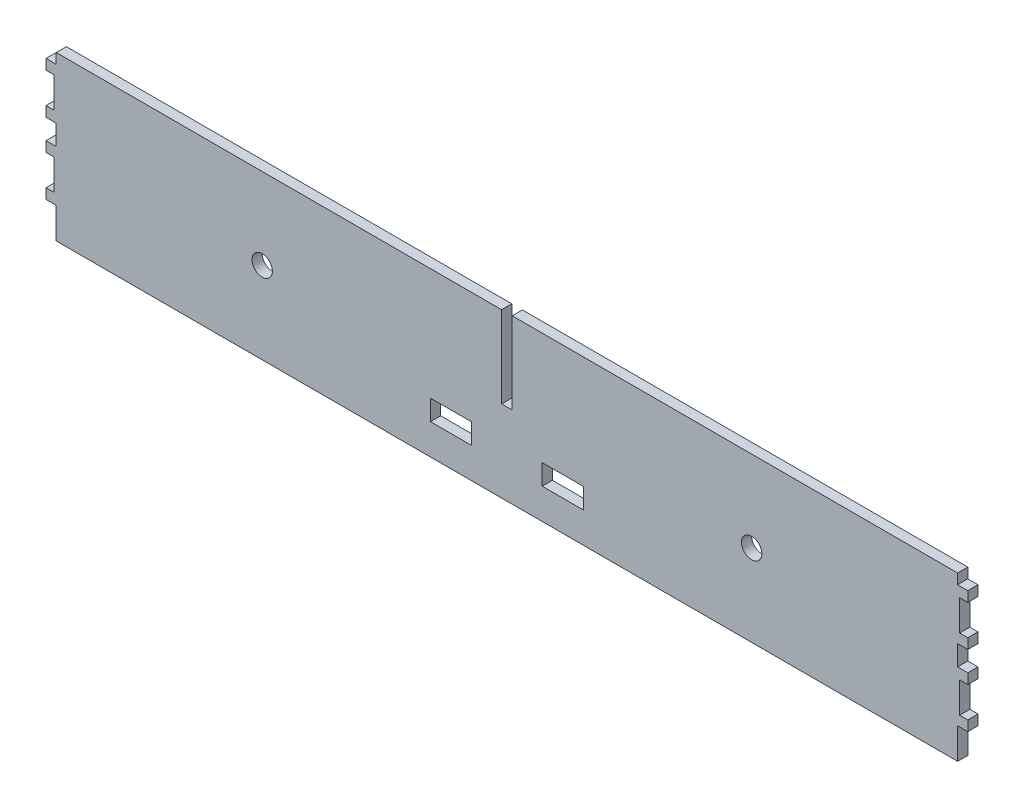
SolidWorks part; units mm, degrees
ref_plane "Front Plane" through (0, 0, 0) normal (0, 0, 1) x (1, 0, 0)
ref_plane "Top Plane" through (0, 0, 0) normal (0, 1, 0) x (1, 0, 0)
ref_plane "Right Plane" through (0, 0, 0) normal (1, 0, 0) x (0, 0, -1)
sketch "Sketch1" plane through (0, 0, 0) normal (0, 0, 1) x (1, 0, 0)
  line L1 (-221, 80) -> (221, 80)
  line L2 (-221, 80) -> (-221, 0)
  line L3 (-221, 0) -> (221, 0)
  line L4 (221, 80) -> (221, 0)
  point P4 (0, 0)
  dimension "D1" = 442
  dimension "D2" = 80
extrude "Boss-Extrude1" add sketch "Sketch1" along normal mid plane 5
sketch "Sketch2" plane through (0, 0, 0) normal (0, 0, 1) x (1, 0, 0)
  line L0 (-221, 0) -> (221, 0) construction
  line L1 (60, 0) -> (-60, 0)
  line L2 (60, 0) -> (60, 8.3333)
  line L3 (58.3333, 10) -> (-58.3333, 10)
  line L4 (-60, 0) -> (-60, 8.3333)
  line L13 (0, -55) -> (0, 55) construction
  arc A3 (-60, 8.3333) -> (-58.3333, 10) centre (-58.3333, 8.3333) cw
  arc A4 (58.3333, 10) -> (60, 8.3333) centre (58.3333, 8.3333) cw
  point P19 (0, 0)
  point P30 (-60, 4.1667)
  dimension "D2" = 60
  dimension "D6" = 10
extrude "Cut-Extrude1" [suppressed] cut sketch "Sketch2" along normal mid plane 5
sketch "Sketch4" plane through (0, 0, 0) normal (0, 0, 1) x (1, 0, 0)
  line L1 (-2.6, 80) -> (2.6, 80)
  line L2 (-2.6, 80) -> (-2.6, 40)
  line L3 (-2.6, 40) -> (2.6, 40)
  line L4 (2.6, 80) -> (2.6, 40)
  line L5 (-2.6, 80) -> (2.6, 40) construction
  line L6 (-2.6, 40) -> (2.6, 80) construction
  line L7 (221, 80) -> (-221, 80) construction
  line L15 (0, -55) -> (0, 55) construction
  point P0 (0, 60)
  dimension "D1" = 40
  dimension "D2" = 5.2
  dimension "D3" = 0
extrude "Cut-Extrude3" cut sketch "Sketch4" against normal through all both and the other way through all
mirror "Mirror6" [suppressed] about plane through (0, 0, 0) normal (1, 0, 0)
sketch "Sketch6" plane through (-221, 0, 0) normal (-1, 0, 0) x (0, 0, 1)
  line L0 (-2.5, 80) -> (-2.5, 0) construction
  line L1 (-2.5, 75) -> (2.5, 75)
  line L2 (-2.5, 75) -> (-2.5, 50)
  line L3 (-2.5, 50) -> (2.5, 50)
  line L4 (2.5, 75) -> (2.5, 50)
  line L5 (2.5, 80) -> (2.5, 0) construction
  line L6 (2.5, 80) -> (-2.5, 80) construction
  line L7 (-2.5, 15.1) -> (2.5, 15.1)
  line L8 (-2.5, 15.1) -> (-2.5, 40.1)
  line L9 (-2.5, 40.1) -> (2.5, 40.1)
  line L10 (2.5, 15.1) -> (2.5, 40.1)
  line L11 (2.6, 40.2) -> (-2.6, 40.2) construction
  dimension "D1" = 5
  dimension "D2" = 0.1
  dimension "D3" = 25
  dimension "D4" = 25
extrude "Boss-Extrude2" add sketch "Sketch6" along normal blind 5
sketch "Sketch7" plane through (-226, 0, 0) normal (-1, 0, 0) x (0, 0, 1)
  line L0 (-2.5, 75) -> (-2.5, 50) construction
  line L1 (-2.5, 70) -> (2.5, 70)
  line L2 (-2.5, 70) -> (-2.5, 55)
  line L3 (-2.5, 55) -> (2.5, 55)
  line L4 (2.5, 70) -> (2.5, 55)
  line L5 (2.5, 50) -> (2.5, 75) construction
  line L6 (-2.5, 40.1) -> (-2.5, 15.1) construction
  line L7 (-2.5, 35.1) -> (2.5, 35.1)
  line L8 (-2.5, 35.1) -> (-2.5, 20.1)
  line L9 (-2.5, 20.1) -> (2.5, 20.1)
  line L10 (2.5, 35.1) -> (2.5, 20.1)
  line L11 (2.5, 15.1) -> (2.5, 40.1) construction
  line L12 (2.5, 75) -> (-2.5, 75) construction
  line L13 (-2.5, 50) -> (2.5, 50) construction
  line L14 (2.5, 40.1) -> (-2.5, 40.1) construction
  line L15 (-2.5, 15.1) -> (2.5, 15.1) construction
  point P24 (0, 15.1)
  dimension "D1" = 5
  dimension "D2" = 5
  dimension "D3" = 5
  dimension "D4" = 5
extrude "Cut-Extrude5" cut sketch "Sketch7" against normal blind 4
mirror "Mirror8" about plane through (0, 0, 0) normal (1, 0, 0) of "Boss-Extrude2", "Cut-Extrude5"
fillet "Fillet1" [suppressed] radius 2
sketch "Sketch8" [suppressed] plane through (0, 0, -2.5) normal (0, 0, -1) x (-1, 0, 0)
  line L0 (-315, 75) -> (-315, 80) construction
  line L1 (-315, 40) -> (-315, 50) construction
  line L2 (-315, 0) -> (-315, 15) construction
  line L3 (-320, 50) -> (-315, 50) construction
  line L4 (0, 2.75) -> (0, -2.75) construction
  circle A0 centre (-315, 76) radius 1
  circle A1 centre (-315, 49) radius 1
  circle A2 centre (-315, 41) radius 1
  circle A3 centre (-315, 14) radius 1
  circle A4 centre (315, 14) radius 1
  circle A5 centre (315, 41) radius 1
  circle A6 centre (315, 49) radius 1
  circle A7 centre (315, 76) radius 1
  dimension "D1" = 2
extrude "Cut-Extrude6" [suppressed] cut sketch "Sketch8" against normal through all
fillet "Fillet2" [suppressed] radius 1
extrude "Cut-Extrude7" cut sketch "Sketch9" against normal blind 300
sketch "Sketch9" plane through (102.7188, -565.4562, 2.5) normal (0, 0, 1) x (1, 0, 0)
  line L4 (-120.0188, 590.4562) -> (-140.2188, 590.4562)
  line L5 (-140.2188, 590.4562) -> (-140.2188, 580.4562)
  line L6 (-120.0188, 580.4562) -> (-140.2188, 580.4562)
  line L7 (-120.0188, 590.4562) -> (-120.0188, 580.4562)
  line L80 (123.2812, 615.4562) -> (123.2812, 620.4562)
  line L81 (123.2812, 620.4562) -> (119.2812, 620.4562)
  line L82 (119.2812, 620.4562) -> (119.2812, 635.4562)
  line L83 (119.2812, 635.4562) -> (123.2812, 635.4562)
  line L84 (123.2812, 635.4562) -> (123.2812, 640.4562)
  line L85 (123.2812, 640.4562) -> (118.2812, 640.4562)
  line L86 (118.2812, 640.4562) -> (118.2812, 645.4562)
  line L87 (118.2812, 645.4562) -> (-100.1188, 645.4562)
  line L88 (-100.1188, 645.4562) -> (-100.1188, 605.4562)
  line L89 (-100.1188, 605.4562) -> (-105.3188, 605.4562)
  line L90 (-105.3188, 605.4562) -> (-105.3188, 645.4562)
  line L91 (-105.3188, 645.4562) -> (-323.7188, 645.4562)
  line L92 (-323.7188, 645.4562) -> (-323.7188, 640.4562)
  line L93 (-323.7188, 640.4562) -> (-328.7188, 640.4562)
  line L94 (-328.7188, 640.4562) -> (-328.7188, 635.4562)
  line L95 (-328.7188, 635.4562) -> (-324.7188, 635.4562)
  line L96 (-324.7188, 635.4562) -> (-324.7188, 620.4562)
  line L97 (-324.7188, 620.4562) -> (-328.7188, 620.4562)
  line L98 (-328.7188, 620.4562) -> (-328.7188, 615.4562)
  line L99 (-328.7188, 615.4562) -> (-323.7188, 615.4562)
  line L100 (-323.7188, 615.4562) -> (-323.7188, 605.5562)
  line L101 (-323.7188, 605.5562) -> (-328.7188, 605.5562)
  line L102 (-328.7188, 605.5562) -> (-328.7188, 600.5562)
  line L103 (-328.7188, 600.5562) -> (-324.7188, 600.5562)
  line L104 (-324.7188, 600.5562) -> (-324.7188, 585.5562)
  line L105 (-324.7188, 585.5562) -> (-328.7188, 585.5562)
  line L106 (-328.7188, 585.5562) -> (-328.7188, 580.5562)
  line L107 (-328.7188, 580.5562) -> (-323.7188, 580.5562)
  line L108 (-323.7188, 580.5562) -> (-323.7188, 565.4562)
  line L109 (-323.7188, 565.4562) -> (118.2812, 565.4562)
  line L110 (118.2812, 565.4562) -> (118.2812, 580.5562)
  line L111 (118.2812, 580.5562) -> (123.2812, 580.5562)
  line L112 (123.2812, 580.5562) -> (123.2812, 585.5562)
  line L113 (123.2812, 585.5562) -> (119.2812, 585.5562)
  line L114 (119.2812, 585.5562) -> (119.2812, 600.5562)
  line L115 (119.2812, 600.5562) -> (123.2812, 600.5562)
  line L116 (123.2812, 600.5562) -> (123.2812, 605.5562)
  line L117 (123.2812, 605.5562) -> (118.2812, 605.5562)
  line L118 (118.2812, 605.5562) -> (118.2812, 615.4562)
  line L119 (118.2812, 615.4562) -> (123.2812, 615.4562)
mirror "Mirror9" about plane through (0, 0, 0) normal (1, 0, 0) of "Cut-Extrude7"
sketch "Sketch10" plane through (0, 0, 2.5) normal (0, 0, 1) x (1, 0, 0)
  line L0 (-221, 40.1) -> (221, 40.1) construction
  line L1 (0, -2.75) -> (0, 2.75) construction
  circle A0 centre (-120, 40.1) radius 5
  circle A1 centre (120, 40.1) radius 5
  dimension "D1" = 10
  dimension "D2" = 120
extrude "Cut-Extrude8" cut sketch "Sketch10" against normal blind 10
